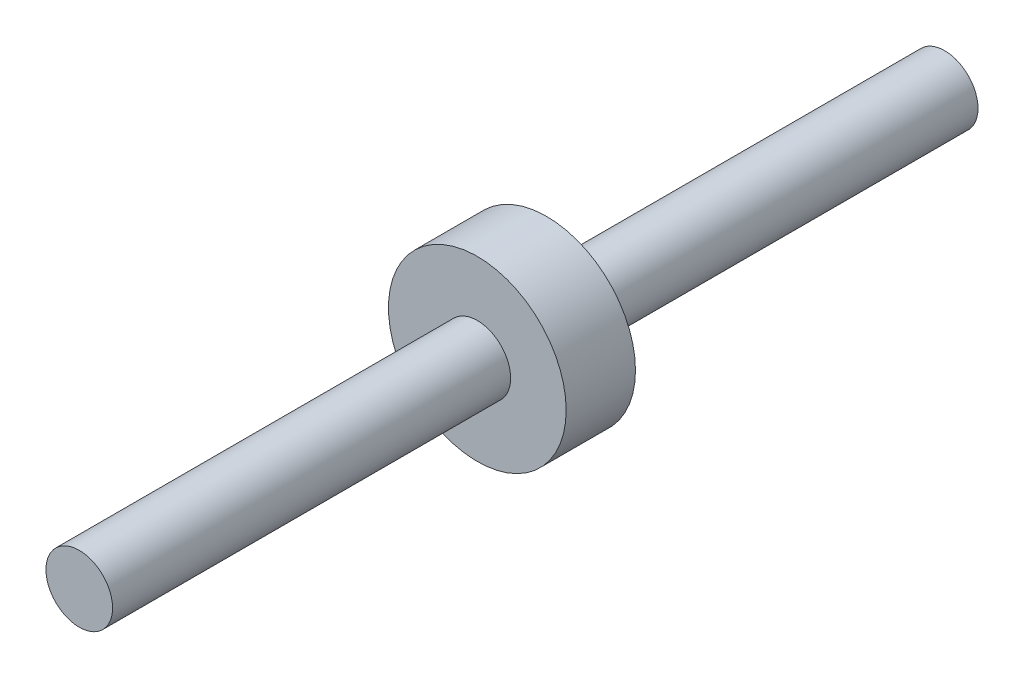
SolidWorks part; units mm, degrees
material "Free-Cutting Brass, UNS C36000"
ref_plane "Front Plane" through (0, 0, 0) normal (0, 0, 1) x (1, 0, 0)
ref_plane "Top Plane" through (0, 0, 0) normal (0, 1, 0) x (1, 0, 0)
ref_plane "Right Plane" through (0, 0, 0) normal (1, 0, 0) x (0, 0, -1)
sketch "Sketch1" plane through (0, 0, 0) normal (0, 0, 1) x (1, 0, 0)
  circle A0 centre (0, 0) radius 4.7625
  dimension "D1" = 9.525
extrude "Boss-Extrude1" add sketch "Sketch1" along normal blind 123.698
ref_plane "Plane1" through (0, 0, 61.849) normal (0, 0, 1) x (1, 0, 0)
sketch "Sketch3" plane through (0, 0, 61.849) normal (0, 0, 1) x (1, 0, 0)
  circle A0 centre (0, 0) radius 12.7
  dimension "D1" = 25.4
extrude "Boss-Extrude2" add sketch "Sketch3" along normal mid plane 9.906
